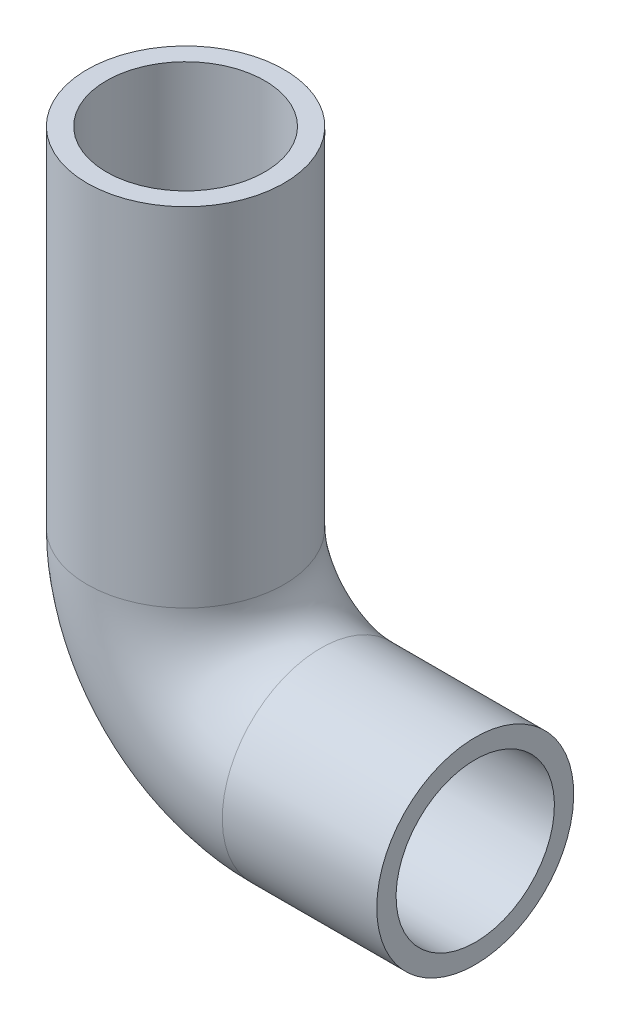
SolidWorks part; units mm, degrees
material "PVC 0.007 Plasticized"
ref_plane "Front Plane" through (0, 0, 0) normal (0, 0, 1) x (1, 0, 0)
ref_plane "Top Plane" through (0, 0, 0) normal (0, 1, 0) x (1, 0, 0)
ref_plane "Right Plane" through (0, 0, 0) normal (1, 0, 0) x (0, 0, -1)
sketch "Sketch1" plane through (0, 0, 0) normal (0, 0, 1) x (1, 0, 0)
  line L0 (0, 250) -> (0, 70)
  line L1 (70, 0) -> (150, 0)
  arc A0 (70, 0) -> (0, 70) centre (70, 70) cw
  point P8 (0, 0)
  dimension "D3" = 70
  dimension "D1" = 250
  dimension "D2" = 150
ref_plane "Plane1" through (0, 250, 0) normal (0, 1, 0) x (1, 0, 0)
sketch "Sketch2" plane through (0, 250, 0) normal (0, 1, 0) x (1, 0, 0)
  circle A0 centre (0, 0) radius 51
  dimension "D1" = 102
sweep "Sweep10" add profiles "Sketch2" path "Sketch1"
shell "Shell1" thickness 10
